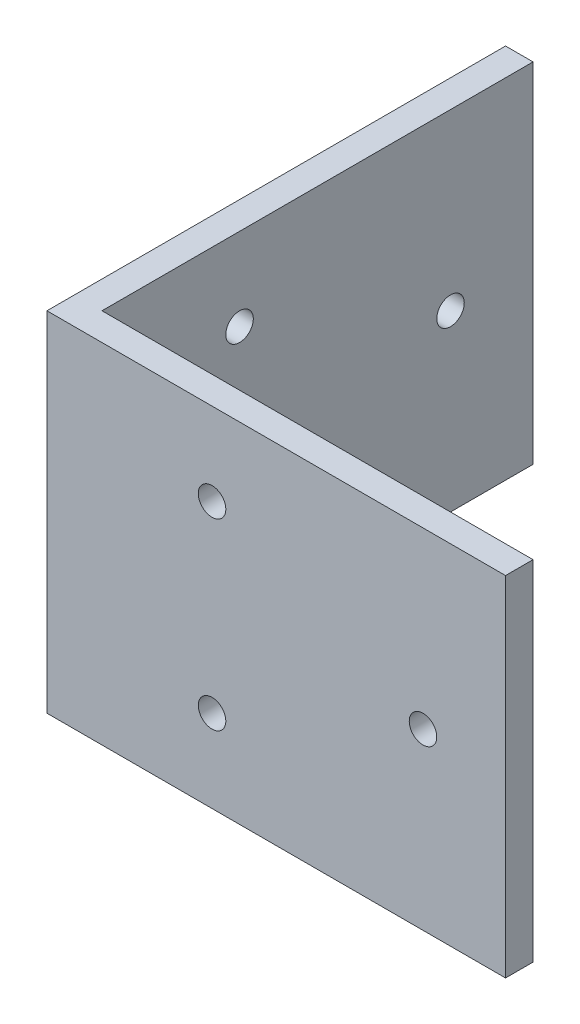
SolidWorks part; units mm, degrees
ref_plane "前视基准面" through (0, 0, 0) normal (0, 0, 1) x (1, 0, 0)
ref_plane "上视基准面" through (0, 0, 0) normal (0, 1, 0) x (1, 0, 0)
ref_plane "右视基准面" through (0, 0, 0) normal (1, 0, 0) x (0, 0, -1)
sketch "草图3" plane through (0, 0, 0) normal (0, 1, 0) x (1, 0, 0)
  line L0 (0, 0) -> (0, -50)
  line L1 (0, -50) -> (50, -50)
  line L2 (50, -50) -> (50, -47)
  line L3 (50, -47) -> (3, -47)
  line L4 (3, -47) -> (3, 0)
  line L5 (3, 0) -> (0, 0)
  dimension "D1" = 3
  dimension "D2" = 3
  dimension "D3" = 50
  dimension "D4" = 50
extrude "凸台-拉伸2" add sketch "草图3" along normal blind 38
sketch "草图4" plane through (3, 0, 0) normal (1, 0, 0) x (0, 0, -1)
  line L0 (-32, 53.2834) -> (-32, -3.2141) construction
  line L1 (-47, 38) -> (-47, 0) construction
  line L2 (-9, 52.868) -> (-9, -3.2141) construction
  line L3 (-47, 38) -> (0, 38) construction
  circle A0 centre (-32, 29) radius 1.5
  circle A1 centre (-32, 9) radius 1.5
  circle A2 centre (-9, 19) radius 1.5
  dimension "D3" = 3
  dimension "D4" = 3
  dimension "D5" = 3
  dimension "D1" = 15
  dimension "D2" = 23
  dimension "D6" = 20
  dimension "D7" = 9
  dimension "D8" = 19
extrude "切除-拉伸1" cut sketch "草图4" against normal blind 50
sketch "草图5" plane through (0, 0, 47) normal (0, 0, -1) x (-1, 0, 0)
  line L0 (-18, 40.1598) -> (-18, -2.4808) construction
  line L1 (-41, 40.1598) -> (-41, -2.4808) construction
  line L2 (-3, 38) -> (-3, 0) construction
  line L3 (-50, 38) -> (-3, 38) construction
  circle A0 centre (-18, 29) radius 1.5
  circle A1 centre (-18, 9) radius 1.5
  circle A2 centre (-41, 19) radius 1.5
  dimension "D3" = 3
  dimension "D4" = 3
  dimension "D7" = 3
  dimension "D1" = 15
  dimension "D2" = 23
  dimension "D5" = 9
  dimension "D6" = 20
  dimension "D8" = 19
extrude "切除-拉伸2" cut sketch "草图5" against normal blind 50
